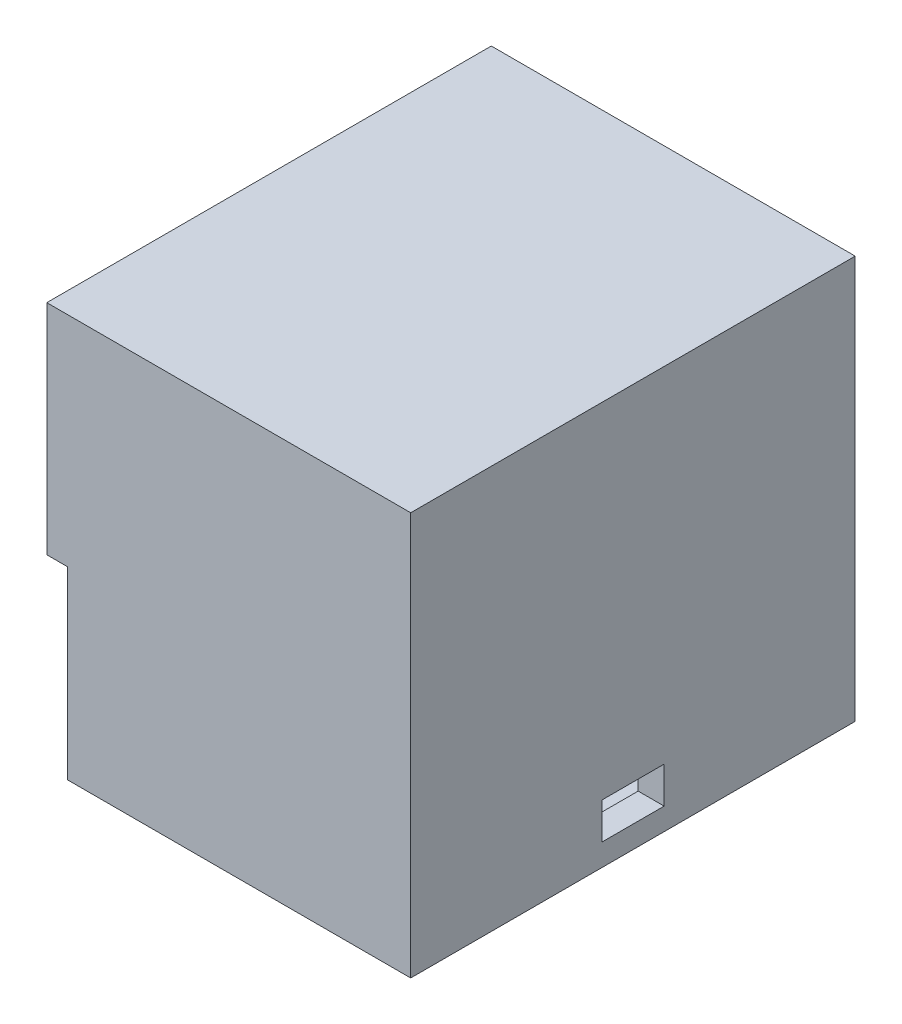
SolidWorks part; units mm, degrees
ref_plane "Front Plane" through (0, 0, 0) normal (0, 0, 1) x (1, 0, 0)
ref_plane "Top Plane" through (0, 0, 0) normal (0, 1, 0) x (1, 0, 0)
ref_plane "Right Plane" through (0, 0, 0) normal (1, 0, 0) x (0, 0, -1)
sketch "Sketch1" plane through (0, 0, 0) normal (0, 0, 1) x (1, 0, 0)
  line L1 (-35, -18.75) -> (35, -18.75)
  line L2 (-35, -18.75) -> (-35, 18.75)
  line L3 (-35, 18.75) -> (35, 18.75)
  line L4 (35, -18.75) -> (35, 18.75)
  line L5 (-35, -18.75) -> (35, 18.75) construction
  line L6 (-35, 18.75) -> (35, -18.75) construction
  point P0 (0, 0)
  dimension "D1" = 37.5
  dimension "70" = 70
extrude "Boss-Extrude1" add sketch "Sketch1" against normal blind 85.5
shell "Shell1" thickness 6
sketch "Sketch4" plane through (0, -12.75, 0) normal (0, 1, 0) x (1, 0, 0)
  line L0 (29, 79.5) -> (29, 6) construction
  line L1 (-29, 79.5) -> (29, 79.5)
  line L2 (-29, 79.5) -> (-29, 77.5)
  line L3 (-29, 77.5) -> (29, 77.5)
  line L4 (29, 79.5) -> (29, 77.5)
  line L5 (29, 42.75) -> (-40.6846, 42.75) construction
  line L6 (-29, 8) -> (29, 8)
  line L7 (29, 6) -> (29, 8)
  line L8 (-29, 6) -> (29, 6)
  line L9 (-29, 6) -> (-29, 8)
  dimension "D1" = 2
extrude "Boss-Extrude2" add sketch "Sketch4" along normal up to surface (31.5 mm away) up to face at (0, 18.75, -42.75)
sketch "Sketch3" plane through (0, 18.75, 0) normal (0, 1, 0) x (1, 0, 0)
  line L9 (-35, 42.75) -> (-65.0617, 42.75) construction
  line L23 (-35, 85.5) -> (-35, 0) construction
  line L30 (-35, 6) -> (29, 6)
  line L46 (35, 85.5) -> (-35, 85.5) construction
  line L47 (-35, 82.5) -> (29, 82.5)
  line L48 (-35, 82.5) -> (-35, 79.5)
  line L49 (-35, 79.5) -> (29, 79.5)
  line L50 (29, 82.5) -> (29, 79.5)
  line L53 (29, 3) -> (29, 6)
  line L54 (-35, 3) -> (29, 3)
  line L55 (-35, 3) -> (-35, 6)
  line M31 (-35, 85.5) -> (-35, 0)
  dimension "D2" = 3
  dimension "D3" = 64
  dimension "D1" = 3
extrude "Cut-Extrude2" cut sketch "Sketch3" against normal blind 2 contours L50 L47 L49 M31
sketch "Sketch6" plane through (0, 18.75, 0) normal (0, 1, 0) x (1, 0, 0)
  line L3 (29, 79.5) -> (29, 6)
  line L4 (29, 79.5) -> (29, 82.5)
  line L5 (29, 6) -> (29, 3)
  line L15 (29, 79.5) -> (-35, 79.5)
  line L16 (-35, 79.5) -> (-35, 6)
  line L17 (-35, 6) -> (29, 6)
  line L18 (29, 6) -> (29, 3)
  line L19 (29, 3) -> (-35, 3)
  line L20 (-35, 3) -> (-35, 0)
  line L21 (-35, 0) -> (35, 0)
  line L22 (35, 0) -> (35, 85.5)
  line L23 (35, 85.5) -> (-35, 85.5)
  line L24 (-35, 85.5) -> (-35, 82.5)
  line L25 (-35, 82.5) -> (29, 82.5)
  line L26 (29, 82.5) -> (29, 79.5)
  line L31 (29, 3) -> (-35, 3)
  line L32 (-35, 3) -> (-35, 0)
  line L33 (-35, 0) -> (35, 0)
  line L34 (35, 0) -> (35, 85.5)
  line L35 (35, 85.5) -> (-35, 85.5)
  line L36 (-35, 85.5) -> (-35, 82.5)
  line L37 (-35, 82.5) -> (29, 82.5)
  dimension "D1" = 0
extrude "Boss-Extrude3" add sketch "Sketch6" along normal blind 40
sketch "Sketch8" plane through (0, 58.75, 0) normal (0, 1, 0) x (1, 0, 0)
  line L1 (29, 82.5) -> (-35, 82.5)
  line L2 (29, 82.5) -> (29, 3)
  line L3 (29, 3) -> (-35, 3)
  line L4 (-35, 82.5) -> (-35, 3)
extrude "Boss-Extrude4" add sketch "Sketch8" against normal blind 4.5
sketch "Sketch9" plane through (-35, 0, 0) normal (-1, 0, 0) x (0, 0, 1)
  line L1 (-81, 15.1115) -> (-4.5, 15.1115)
  line L2 (-81, 15.1115) -> (-81, -17.0564)
  line L3 (-81, -17.0564) -> (-4.5, -17.0564)
  line L4 (-4.5, 15.1115) -> (-4.5, -17.0564)
  line L7 (-82.5, 16.75) -> (-79.5, 16.75) construction
  line L8 (-3, 16.75) -> (-6, 16.75) construction
  point P6 (-81, 16.75)
  point P9 (-4.5, 16.75)
extrude "Cut-Extrude3" cut sketch "Sketch9" against normal blind 65
sketch "Sketch10" plane through (-35, 0, 0) normal (-1, 0, 0) x (0, 0, 1)
  line L3 (-42.75, 58.75) -> (-42.75, -56.2387) construction
  line L4 (-85.5, 58.75) -> (0, 58.75) construction
  line L5 (-81, -17.0564) -> (-85.5, -17.0564) construction
  line L6 (-85.5, 58.75) -> (-85.5, 16.75) construction
  line L8 (-4.5, 15.1115) -> (0, 15.1115) construction
  line L9 (0, 58.75) -> (0, 16.75) construction
  line L10 (-4.5, 15.1115) -> (-81, 15.1115) construction
  line L11 (-85.5, -18.75) -> (0, -18.75) construction
  line L12 (-3, 16.75) -> (-6, 16.75) construction
  circle A0 centre (-2.25, 13.25) radius 1
  circle A3 centre (-83.25, 13.25) radius 1
  circle A4 centre (-83.25, -16.5) radius 1
  circle A5 centre (-2.25, -16.5) radius 1
  point P0 (-2.25, 13.25)
  point P15 (-83.25, -16.5)
  point P19 (-83.25, 13.25)
  point P24 (-83.25, -17.0564)
  point P25 (-2.25, -16.5)
  point P54 (-2.25, 15.1115)
  dimension "D1" = 3.5
  dimension "2" = 2
  dimension "D2" = 2.25
  dimension "D3" = 2.25
sketch "Sketch14" plane through (-35, 0, 0) normal (-1, 0, 0) x (0, 0, 1)
  line L0 (-85.5, 58.75) -> (-85.5, -18.75) construction
  line L1 (0, -18.75) -> (-85.5, -18.75)
  line L2 (0, -18.75) -> (0, 16.75)
  line L3 (0, 16.75) -> (-85.5, 16.75)
  line L4 (-85.5, -18.75) -> (-85.5, 16.75)
extrude "Cut-Extrude4" cut sketch "Sketch14" against normal blind 4
hole_wizard "M2 Tapped Hole1" positions "Sketch10" profile "Sketch13" tap size "M2" standard "ISO"
sketch "Sketch13" plane through (-35, 13.25, -2.25) normal (0, 1, 0) x (0, 0, 1)
  line L0 (0, 0) -> (0, 4.4807)
  line L1 (0, 4.4807) -> (0.8, 4)
  line L2 (0.8, 4) -> (0.8, 0)
  line L5 (0.8, 0) -> (0, 0)
  line L10 (0, 4.4807) -> (-0.8, 4) construction
  line L11 (0, -6.35) -> (0, 107.95) construction
  dimension "Tap Drill Dia." = 1.6
  dimension "Tap Drill Depth" = 4
  dimension "Drill Angle" = 118
cosmetic thread "Hole Thread1" parameters "D1"=4, "D2"=3.6602
cosmetic thread "Hole Thread2" parameters "D1"=4, "D2"=3.6602
cosmetic thread "Hole Thread3" parameters "D1"=4, "D2"=3.6602
cosmetic thread "Hole Thread4" parameters "D1"=4, "D2"=3.6602
sketch "Sketch15" plane through (-31, 0, 0) normal (-1, 0, 0) x (0, 0, 1)
  circle A0 centre (-2.25, 13.25) radius 1.4097
  circle A1 centre (-2.25, -16.5) radius 1.5797
  circle A2 centre (-83.25, -16.5) radius 1.3335
  circle A3 centre (-83.25, 13.25) radius 1.4437
  point P0 (-2.25, 13.25)
  point P3 (-2.25, -16.5)
  point P6 (-83.25, -16.5)
  point P9 (-83.25, 13.25)
hole_wizard "M2 Tapped Hole2" positions "Sketch15" profile "Sketch16" tap size "M2" standard "ISO"
sketch "Sketch16" plane through (-31, 13.25, -2.25) normal (0, 1, 0) x (0, 0, 1)
  line L0 (0, 0) -> (0, 4.4807)
  line L1 (0, 4.4807) -> (0.8, 4)
  line L2 (0.8, 4) -> (0.8, 0)
  line L5 (0.8, 0) -> (0, 0)
  line L10 (0, 4.4807) -> (-0.8, 4) construction
  line L11 (0, -6.35) -> (0, 107.95) construction
  dimension "Tap Drill Dia." = 1.6
  dimension "Tap Drill Depth" = 4
  dimension "Drill Angle" = 118
cosmetic thread "Hole Thread5" parameters "D1"=4, "D2"=2
cosmetic thread "Hole Thread6" parameters "D1"=4, "D2"=2
cosmetic thread "Hole Thread7" parameters "D1"=4, "D2"=2
cosmetic thread "Hole Thread8" parameters "D1"=4, "D2"=2
sketch "Sketch17" plane through (35, 0, 0) normal (1, 0, 0) x (0, 0, -1)
  line L0 (42.75, 58.75) -> (42.75, -7.4932) construction
  line L1 (36.75, -7.4932) -> (48.75, -7.4932)
  line L2 (36.75, -7.4932) -> (36.75, -14.4932)
  line L3 (36.75, -14.4932) -> (48.75, -14.4932)
  line L4 (48.75, -7.4932) -> (48.75, -14.4932)
  line L5 (0, 58.75) -> (85.5, 58.75) construction
  dimension "D1" = 12
  dimension "D2" = 7
extrude "Cut-Extrude5" cut sketch "Sketch17" against normal blind 10
sketch "Sketch19" plane through (-31, 0, 0) normal (-1, 0, 0) x (0, 0, 1)
  line L0 (-81, -17.0564) -> (-81, 15.1115) construction
  line L1 (-81, 2.4115) -> (-57, 2.4115)
  line L2 (-81, 2.4115) -> (-81, -1.5885)
  line L3 (-81, -1.5885) -> (-57, -1.5885)
  line L4 (-57, 2.4115) -> (-57, -1.5885)
  line L5 (-81, 15.1115) -> (-4.5, 15.1115) construction
  dimension "D1" = 12.7
  dimension "D2" = 4
  dimension "D3" = 24
extrude "Boss-Extrude5" add sketch "Sketch19" against normal up to surface (61 mm away) up to face at (30, -10.9932, -42.75)
sketch "Sketch20" plane through (0, 0, -81) normal (0, 0, 1) x (1, 0, 0)
  line L0 (-31, -18.75) -> (-31, 16.75) construction
  line L1 (-10, 2.4115) -> (13.5, 2.4115)
  line L2 (-10, 2.4115) -> (-10, 11.9383)
  line L3 (-10, 11.9383) -> (13.5, 11.9383)
  line L4 (13.5, 2.4115) -> (13.5, 11.9383)
  line L5 (1.75, 2.4115) -> (1.75, 5.4654) construction
  line L6 (-10, 2.4115) -> (-15.5, 2.4115)
  line L7 (-10, 2.4115) -> (-10, 11.9383)
  line L8 (-10, 11.9383) -> (-15.5, 11.9383)
  line L9 (-15.5, 2.4115) -> (-15.5, 11.9383)
  line L10 (13.5, 2.4115) -> (19, 2.4115)
  line L11 (13.5, 2.4115) -> (13.5, 11.9383)
  line L12 (13.5, 11.9383) -> (19, 11.9383)
  line L13 (19, 2.4115) -> (19, 11.9383)
  line L14 (30, 2.4115) -> (-31, 2.4115) construction
  dimension "D1" = 21
  dimension "D2" = 23.5
  dimension "D3" = 5.5
extrude "Boss-Extrude7" add sketch "Sketch20" along normal blind 17 contours L10 L13 L12 L4 | L9 L6 L2 L8
sketch "Sketch21" plane through (-31, 0, 0) normal (-1, 0, 0) x (0, 0, 1)
  line L1 (-57, 2.4115) -> (-81, 2.4115)
  line L2 (-57, 2.4115) -> (-57, -1.5885)
  line L3 (-57, -1.5885) -> (-81, -1.5885)
  line L4 (-81, 2.4115) -> (-81, -1.5885)
extrude "Cut-Extrude6" cut sketch "Sketch21" against normal up to surface (15.5 mm away) up to face at (-15.5, 7.1749, -72.5)
